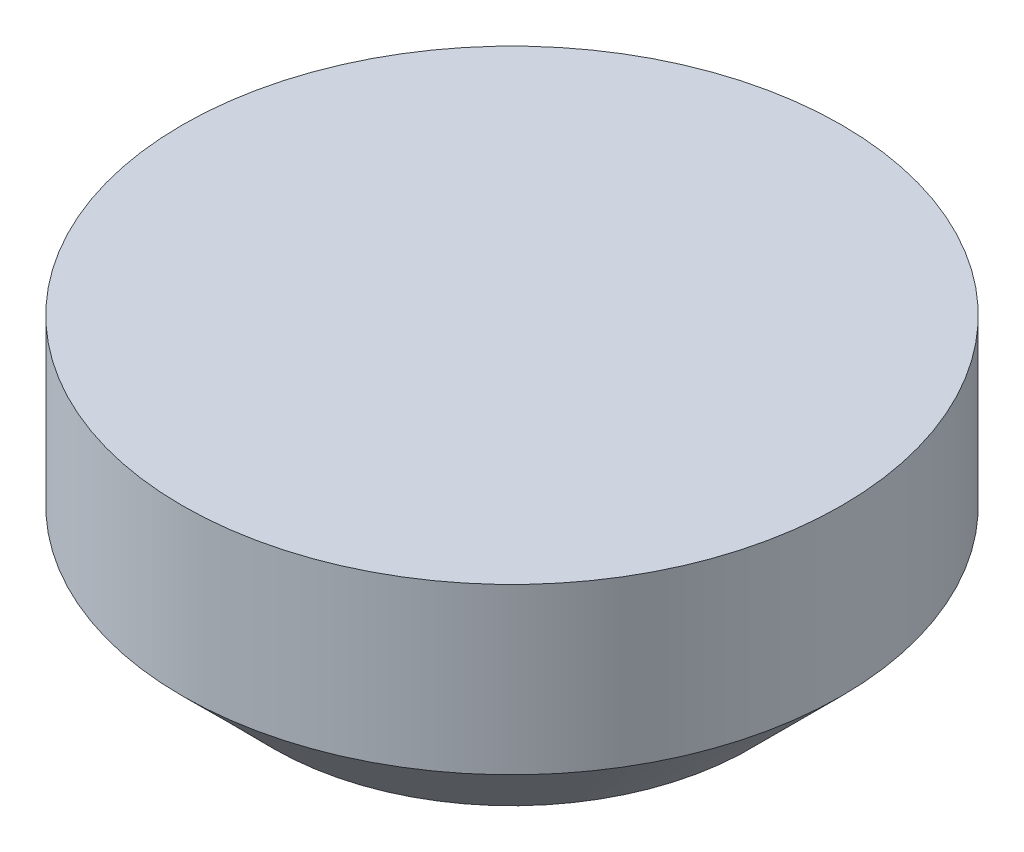
SolidWorks part; units mm, degrees
ref_plane "Спереди" through (0, 0, 0) normal (0, 0, 1) x (1, 0, 0)
ref_plane "Сверху" through (0, 0, 0) normal (0, 1, 0) x (1, 0, 0)
ref_plane "Справа" through (0, 0, 0) normal (1, 0, 0) x (0, 0, -1)
sketch "Эскиз1" plane through (0, 0, 0) normal (0, 0, 1) x (1, 0, 0)
  line L0 (0, 0) -> (-9, 0)
  line L1 (-9, 0) -> (-9, -4.5)
  line L2 (-9, -4.5) -> (-6.5, -7)
  line L3 (-6.5, -7) -> (-6, -7)
  line L4 (-6, -7) -> (-6, -2)
  line L5 (-6, -2) -> (0, -2)
  line L6 (0, -2) -> (0, 0)
  dimension "D1" = 9
  dimension "D2" = 4.5
  dimension "D3" = 5
  dimension "D4" = 6
  dimension "D5" = 2
  dimension "D6" = 6.5
revolve "Повернуть1" add sketch "Эскиз1" angle 360 about L6
